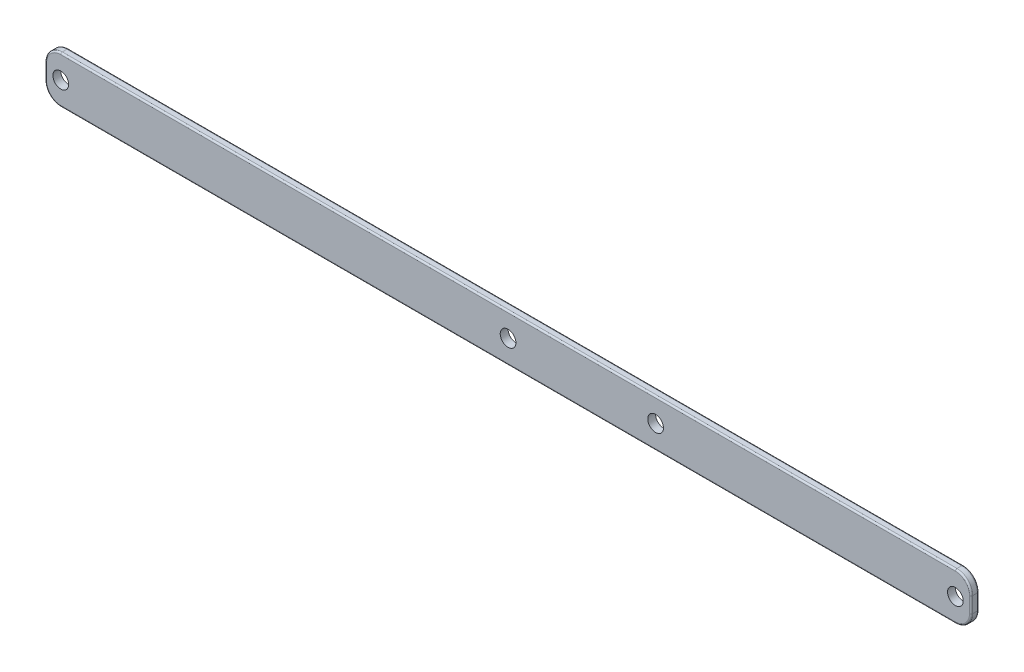
SolidWorks part; units mm, degrees
ref_plane "정면" through (0, 0, 0) normal (0, 0, 1) x (1, 0, 0)
ref_plane "윗면" through (0, 0, 0) normal (0, 1, 0) x (1, 0, 0)
ref_plane "우측면" through (0, 0, 0) normal (1, 0, 0) x (0, 0, -1)
sketch "스케치1" plane through (0, 0, 0) normal (0, 0, 1) x (1, 0, 0)
  line L1 (-289.3224, 55.1673) -> (300.6776, 55.1673)
  line L2 (-289.3224, 55.1673) -> (-289.3224, 25.1673)
  line L3 (-289.3224, 25.1673) -> (300.6776, 25.1673)
  line L4 (300.6776, 55.1673) -> (300.6776, 25.1673)
  circle A0 centre (-279.3224, 40.1673) radius 5
  circle A1 centre (290.6776, 40.1673) radius 5
  circle A2 centre (5.6776, 40.1673) radius 5
  point P11 (300.6776, 40.1673)
  point P12 (5.6776, 25.1673)
  dimension "D3" = 10
  dimension "D4" = 10
  dimension "D5" = 10
  dimension "D1" = 590
  dimension "D2" = 30
  dimension "D6" = 10
  dimension "D7" = 10
extrude "보스-돌출1" add sketch "스케치1" along normal blind 5
fillet "필렛1" radius 10 4 edges at (300.6776, 25.1673, 2.5) (300.6776, 55.1673, 2.5) (-289.3224, 25.1673, 2.5) (-289.3224, 55.1673, 2.5)
fillet "필렛2" radius 1 16 edges at (300.6776, 40.1673, 5) (297.7487, 28.0963, 5) (5.6776, 25.1673, 5) (-286.3935, 28.0963, 5) (-289.3224, 40.1673, 5) (-286.3935, 52.2384, 5) (5.6776, 55.1673, 5) (297.7487, 52.2384, 0) (5.6776, 55.1673, 0) (-286.3935, 52.2384, 0) (-289.3224, 40.1673, 0) (-286.3935, 28.0963, 0) (5.6776, 25.1673, 0) (297.7487, 28.0963, 0) (300.6776, 40.1673, 0) (297.7487, 52.2384, 5)
sketch "스케치2" plane through (0, 0, 5) normal (0, 0, 1) x (1, 0, 0)
  line L0 (299.6776, 35.1673) -> (299.6776, 45.1673) construction
  circle A0 centre (99.6776, 40.1673) radius 5
  point P5 (299.6776, 40.1673)
  dimension "D1" = 10
  dimension "D2" = 200
extrude "컷-돌출1" cut sketch "스케치2" against normal up to next
